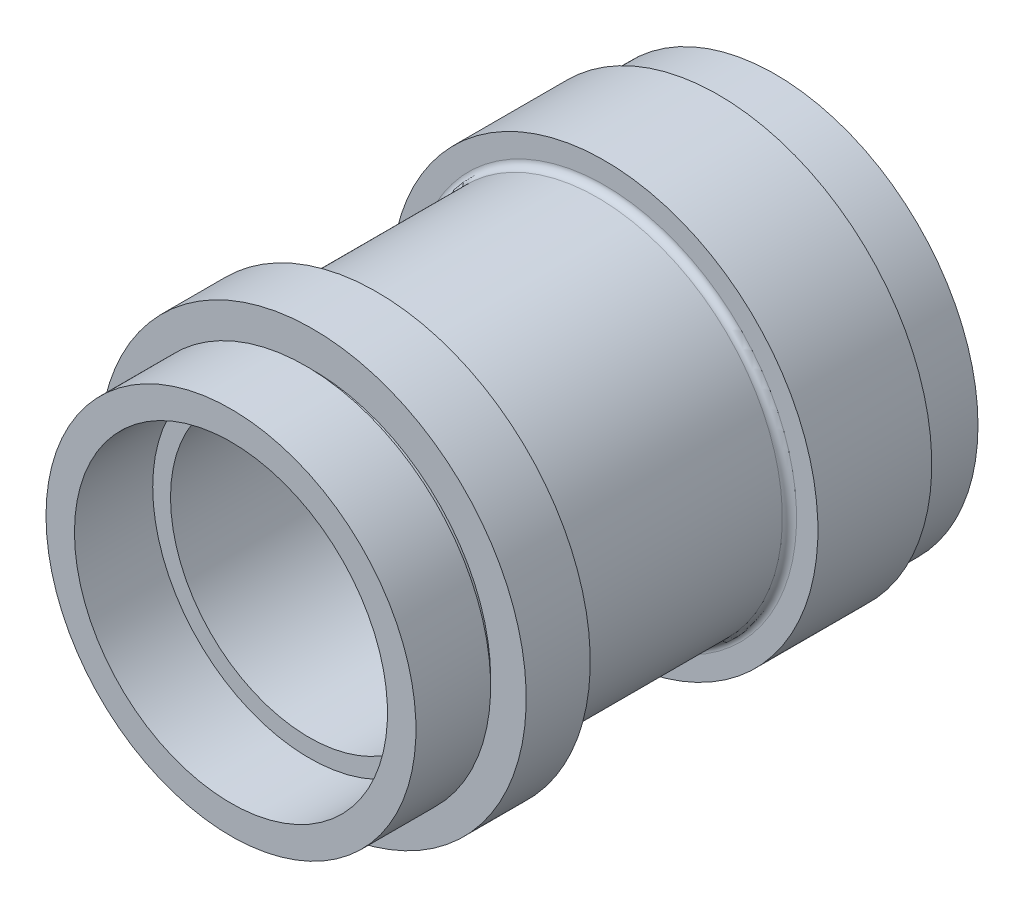
SolidWorks part; units mm, degrees
ref_plane "Plan de face" through (0, 0, 0) normal (0, 0, 1) x (1, 0, 0)
ref_plane "Plan de dessus" through (0, 0, 0) normal (0, 1, 0) x (1, 0, 0)
ref_plane "Plan de droite" through (0, 0, 0) normal (1, 0, 0) x (0, 0, -1)
sketch "Esquisse1" plane through (0, 0, 0) normal (0, 0, 1) x (1, 0, 0)
  circle A0 centre (0, 0) radius 14.25
  dimension "D1" = 28.5
extrude "Boss.-Extru.1" add sketch "Esquisse1" along normal blind 4
sketch "Esquisse2" plane through (0, 0, 4) normal (0, 0, 1) x (1, 0, 0)
  circle A0 centre (0, 0) radius 15
  dimension "D1" = 30
extrude "Boss.-Extru.2" add sketch "Esquisse2" along normal blind 28.5
sketch "Esquisse3" plane through (0, 0, 32.5) normal (0, 0, 1) x (1, 0, 0)
  circle A0 centre (0, 0) radius 12.5
  dimension "D1" = 25
extrude "Boss.-Extru.3" add sketch "Esquisse3" along normal blind 0.5
sketch "Esquisse4" plane through (0, 0, 33) normal (0, 0, 1) x (1, 0, 0)
  circle A0 centre (0, 0) radius 13
  dimension "D1" = 26
extrude "Boss.-Extru.4" add sketch "Esquisse4" along normal blind 5.25
cosmetic thread "Représentation de filetage1" parameters "D2"=25
sketch "Esquisse5" plane through (0, 0, 0) normal (1, 0, 0) x (0, 0, -1)
  line L0 (0, 0) -> (-38.25, 0)
  line L1 (-38.25, 13) -> (-38.25, -13) construction
  line L2 (-32.75, 9.75) -> (-32.75, 11)
  line L4 (0, 0) -> (0, 9.75)
  line L5 (0, 9.75) -> (-32.75, 9.75)
  line L7 (-32.75, 11) -> (-38.25, 11)
  line L8 (-38.25, 11) -> (-38.25, 0)
  line L10 (-28, 15) -> (-12, 15)
  line L11 (-28, 15) -> (-28, 13.5)
  line L12 (-27.5, 13) -> (-12.5, 13)
  line L13 (-12, 15) -> (-12, 13.5)
  line L14 (-32.5, 15) -> (-32.5, -15) construction
  arc A0 (-12.5, 13) -> (-12, 13.5) centre (-12.5, 13.5) ccw
  arc A1 (-27.5, 13) -> (-28, 13.5) centre (-27.5, 13.5) cw
  point P13 (-24.7533, 13.0712)
  point P14 (0, 0)
  point P15 (-32.5, 12.0986)
  point P16 (-32.5, 12.4228)
  point P19 (0, 0)
  point P20 (0, 0)
  point P21 (0, 0)
  point P26 (-28, 13)
  dimension "D7" = 0.5
  dimension "D1" = 9.75
  dimension "D2" = 32.75
  dimension "D3" = 4.5
  dimension "D4" = 1.25
  dimension "D5" = 16
  dimension "D6" = 2
revolve "Enlèvement de matière-Révolution1" cut sketch "Esquisse5" angle 360 about L0
sketch "Esquisse11" plane through (0, 0, 0) normal (0, 0, -1) x (-1, 0, 0)
  line L1 (0, 12.75) -> (0, 14.25) construction
  circle A0 centre (0, 0) radius 14.25 construction
  circle A1 centre (0, 0) radius 14.25 construction
  point P2 (0, 12.75)
  point P12 (0, 12.75)
  dimension "D1" = 1.5
hole_wizard "Diamètre du perçage Ø2.0 (2)1" positions "Esquisse11" profile "Esquisse10" hole size "Ø2.0" standard "ISO"
sketch "Esquisse10" plane through (0, 12.75, 0) normal (1, 0, 0) x (0, 1, 0)
  line L0 (0, 0) -> (0, 9.6009)
  line L1 (0, 9.6009) -> (1, 9)
  line L2 (1, 9) -> (1, 0)
  line L5 (1, 0) -> (0, 0)
  line L10 (0, 9.6009) -> (-1, 9) construction
  line L11 (0, -6.35) -> (0, 107.95) construction
  dimension "Diamètre du perçage" = 2
  dimension "Profondeur du perçage" = 9
  dimension "Angle de pointe" = 118
